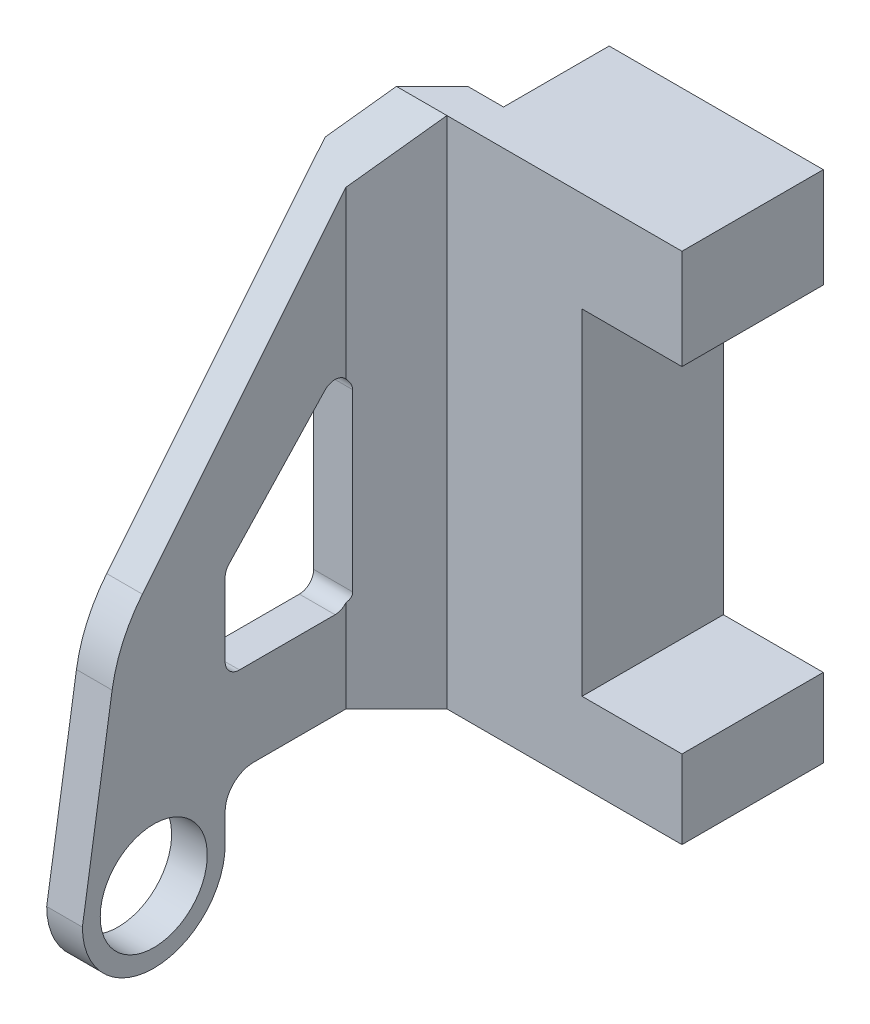
SolidWorks part; units mm, degrees
ref_plane "Płaszczyzna przednia" through (0, 0, 0) normal (0, 0, 1) x (1, 0, 0)
ref_plane "Płaszczyzna górna" through (0, 0, 0) normal (0, 1, 0) x (1, 0, 0)
ref_plane "Płaszczyzna prawa" through (0, 0, 0) normal (1, 0, 0) x (0, 0, -1)
sketch "Szkic1" plane through (0, 0, 0) normal (0, 0, 1) x (1, 0, 0)
  line L0 (0, 0) -> (0, 36)
  line L1 (0, 36) -> (-15, 36)
  line L2 (-15, 36) -> (-15, 0)
  line L3 (-15, 0) -> (0, 0)
  dimension "D1" = 15
  dimension "D2" = 36
extrude "Dodanie-wyciągnięcie1" add sketch "Szkic1" along normal blind 9.9
sketch "Szkic2" plane through (0, 0, 9.9) normal (0, 0, 1) x (1, 0, 0)
  line L0 (0, 29) -> (-7, 29)
  line L1 (0, 0) -> (0, 36) construction
  line L2 (-7, 29) -> (-7, 5.5)
  line L3 (-7, 5.5) -> (0, 5.5)
  line L4 (0, 5.5) -> (0, 29)
  line L5 (0, 36) -> (-15, 36) construction
  dimension "D1" = 7
  dimension "D2" = 23.5
  dimension "D3" = 7
extrude "Wytnij-wyciągnięcie1" cut sketch "Szkic2" against normal blind 9.9
sketch "Szkic3" plane through (-15, 0, 0) normal (-1, 0, 0) x (0, 0, 1)
  line L0 (7.4, 36) -> (9.9, 36) construction
  line L1 (7.4, 0) -> (7.4, 36) construction
  line L2 (9.9, 36) -> (12.4, 32.9231) construction
  line L3 (29.4, 12) -> (12.4, 32.9231) construction
  line L4 (31.9, -4) -> (29.4, 12) construction
  line L5 (21.9, 0) -> (21.9, -4) construction
  line L6 (12.4, 0) -> (21.9, 0) construction
  line L7 (7.4, 0) -> (12.4, 0) construction
  line L8 (7.4, 36) -> (9.9, 36)
  line L9 (7.4, 0) -> (7.4, 36)
  line L10 (9.9, 36) -> (12.4, 32.9231)
  line L11 (29.4, 12) -> (12.4, 32.9231)
  line L12 (31.9, -4) -> (29.4, 12)
  line L13 (21.9, 0) -> (21.9, -4)
  line L14 (12.4, 0) -> (21.9, 0)
  line L15 (7.4, 0) -> (12.4, 0)
  circle A0 centre (26.9, -4) radius 2.5 construction
  arc A1 (21.9, -4) -> (31.9, -4) centre (26.9, -4) ccw construction
  circle A2 centre (26.9, -4) radius 2.5
  arc A3 (21.9, -4) -> (31.9, -4) centre (26.9, -4) ccw
extrude "Dodanie-wyciągnięcie2" add sketch "Szkic3" along normal blind 7.5
sketch "Szkic4" plane through (0, 36, 0) normal (0, 1, 0) x (1, 0, 0)
  line L0 (-17.5, -7.4) -> (-25.0011, -14.9011)
  line L1 (-22.5, -7.4) -> (-15, -7.4) construction
  line L2 (-15, -7.4) -> (-15, 0) construction
  line L3 (-17.5, -7.4) -> (-26.526, -7.4)
  line L4 (-26.526, -7.4) -> (-25.0011, -14.9011)
  line L5 (-16.4645, -9.9) -> (-20, -13.4355)
  line L6 (-22.5, -9.9) -> (-15, -9.9) construction
  line L7 (-20, -13.4355) -> (-20, -34.971)
  line L8 (-20, -34.971) -> (-2.8566, -34.971)
  line L9 (-2.8566, -34.971) -> (-4.3843, -9.9)
  line L10 (0, -9.9) -> (-15, -9.9) construction
  line L11 (-4.3843, -9.9) -> (-16.4645, -9.9)
  line L12 (-22.5, -29.4) -> (-22.5, -9.9) construction
  dimension "D1" = 45
  dimension "D2" = 2.5
  dimension "D3" = 2.5
  dimension "D4" = 2.5
extrude "Wytnij-wyciągnięcie2" cut sketch "Szkic4" against normal blind 137.5
sketch "Szkic5" plane through (-22.5, 0, 0) normal (-1, 0, 0) x (0, 0, 1)
  line L0 (21.9, 12.2052) -> (21.9, 7.1) construction
  line L1 (21.9, 12.2052) -> (21.9, 7.1)
  line L2 (20.9, 6.1) -> (14.2, 6.1) construction
  line L3 (13.2, 7.1) -> (13.2, 19.3672) construction
  line L4 (14.9303, 20.0504) -> (21.6303, 12.8883) construction
  line L5 (12.4, 32.9231) -> (12.4, 0)
  line L6 (12.4, 0) -> (21.9, 0)
  line L7 (21.9, 0) -> (21.9, -4)
  line L8 (31.9, -4) -> (29.4, 12)
  line L9 (29.4, 12) -> (12.4, 32.9231)
  line L10 (12.4, 32.9231) -> (12.4, 0)
  line L11 (12.4, 0) -> (21.9, 0)
  line L12 (21.9, 0) -> (21.9, -4)
  line L13 (31.9, -4) -> (29.4, 12)
  line L14 (29.4, 12) -> (12.4, 32.9231)
  line L15 (20.9, 6.1) -> (14.2, 6.1)
  line L16 (13.2, 7.1) -> (13.2, 19.3672)
  line L17 (14.9303, 20.0504) -> (21.6303, 12.8883)
  arc A0 (21.9, 12.2052) -> (21.6303, 12.8883) centre (20.9, 12.2052) ccw construction
  arc A1 (21.9, -4) -> (31.9, -4) centre (26.9, -4) ccw
  arc A2 (21.9, -4) -> (31.9, -4) centre (26.9, -4) ccw
  arc A3 (21.9, 12.2052) -> (21.6303, 12.8883) centre (20.9, 12.2052) ccw
  arc A4 (20.9, 6.1) -> (21.9, 7.1) centre (20.9, 7.1) ccw construction
  arc A5 (13.2, 7.1) -> (14.2, 6.1) centre (14.2, 7.1) ccw construction
  arc A6 (14.9303, 20.0504) -> (13.2, 19.3672) centre (14.2, 19.3672) ccw construction
  arc A7 (20.9, 6.1) -> (21.9, 7.1) centre (20.9, 7.1) ccw
  arc A8 (13.2, 7.1) -> (14.2, 6.1) centre (14.2, 7.1) ccw
  arc A9 (14.9303, 20.0504) -> (13.2, 19.3672) centre (14.2, 19.3672) ccw
  dimension "D1" = 0
extrude "Wytnij-wyciągnięcie3" cut sketch "Szkic5" against normal blind 137.5 contours L17 A9 L16 A8 L15 A7 L1 A3
fillet "Zaokrąglenie1" radius 10 1 edges at (-21.25, 12, 29.4)
fillet "Zaokrąglenie2" radius 2 1 edges at (-21.25, 0, 21.9)
sketch "Szkic6" plane through (-22.5, 0, 0) normal (-1, 0, 0) x (0, 0, 1)
  circle A0 centre (26.9, -4) radius 3.75
  dimension "D1" = 7.5
extrude "Wytnij-wyciągnięcie4" cut sketch "Szkic6" against normal blind 10
